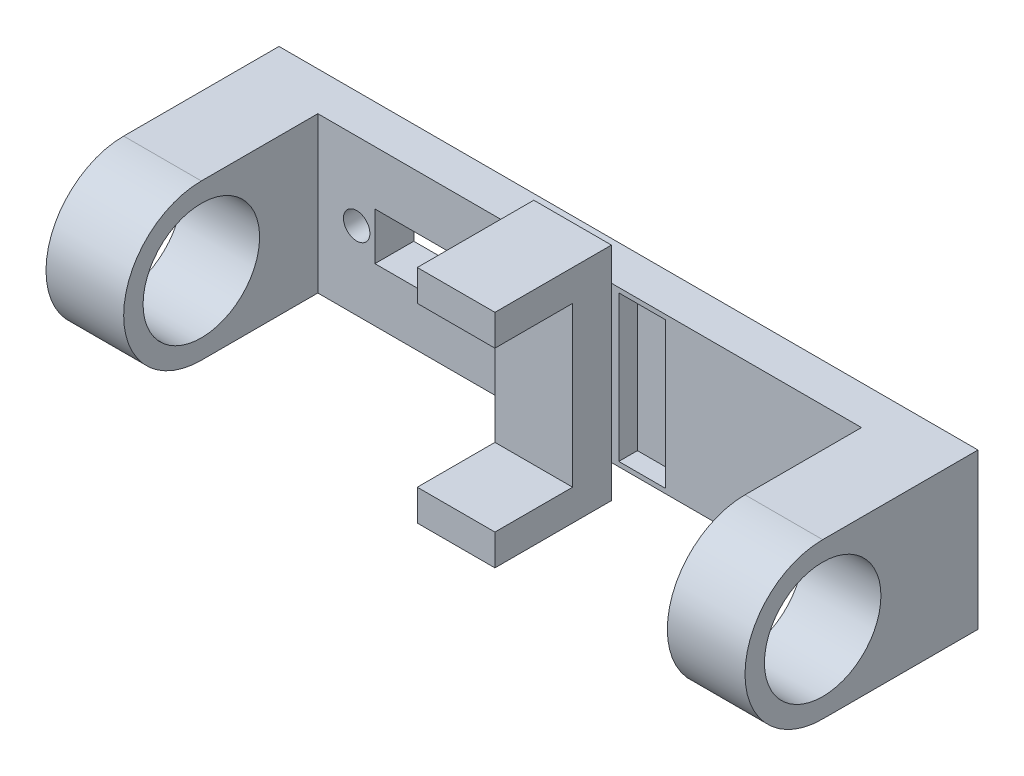
SolidWorks part; units mm, degrees
ref_plane "Plan de face" through (0, 0, 0) normal (0, 0, 1) x (1, 0, 0)
ref_plane "Plan de dessus" through (0, 0, 0) normal (0, 1, 0) x (1, 0, 0)
ref_plane "Plan de droite" through (0, 0, 0) normal (1, 0, 0) x (0, 0, -1)
sketch "Esquisse1" plane through (0, 0, 0) normal (0, 0, 1) x (1, 0, 0)
  line L1 (0, 0) -> (90, 0)
  line L2 (0, 0) -> (0, 20)
  line L3 (0, 20) -> (90, 20)
  line L4 (90, 0) -> (90, 20)
  dimension "D1" = 90
  dimension "D2" = 20
extrude "Boss.-Extru.1" add sketch "Esquisse1" along normal blind 5
sketch "Esquisse2" plane through (0, 0, 5) normal (0, 0, 1) x (1, 0, 0)
  line L0 (90, 20) -> (0, 20) construction
  line L1 (0, 0) -> (10, 0)
  line L2 (0, 0) -> (0, 20)
  line L3 (0, 20) -> (10, 20)
  line L4 (10, 0) -> (10, 20)
  dimension "D1" = 10
extrude "Boss.-Extru.2" add sketch "Esquisse2" along normal blind 30
sketch "Esquisse3" plane through (0, 0, 0) normal (-1, 0, 0) x (0, 0, 1)
  line L0 (0, 20) -> (0, 0) construction
  line L1 (35, 20) -> (0, 20) construction
  line L2 (35, 20) -> (35, 0) construction
  line L3 (35, 0) -> (0, 0) construction
  line L4 (35, 20) -> (20, 20)
  line L5 (35, 20) -> (35, 0)
  line L6 (35, 0) -> (20, 0)
  circle A0 centre (20, 10) radius 7.5
  arc A1 (20, 0) -> (20, 20) centre (20, 10) ccw
  dimension "D2" = 15
  dimension "D4" = 20
  dimension "D1" = 20
  dimension "D3" = 10
extrude "Enlèv. mat.-Extru.1" cut sketch "Esquisse3" against normal up to surface (10 mm away) up to face at (10, 10, 20)
ref_plane "Plan1" through (45, 0, 0) normal (1, 0, 0) x (0, 0, -1)
mirror "Symétrie1" about plane through (45, 0, 0) normal (1, 0, 0) of "Enlèv. mat.-Extru.1", "Boss.-Extru.2"
sketch "Esquisse5" plane through (0, 0, 5) normal (0, 0, 1) x (1, 0, 0)
  line L0 (80, 20) -> (10, 20) construction
  line L1 (48.75, 19.4) -> (54.75, 19.4)
  line L2 (48.75, 19.4) -> (48.75, 0.6)
  line L3 (48.75, 0.6) -> (54.75, 0.6)
  line L4 (54.75, 19.4) -> (54.75, 0.6)
  line L10 (45, -11) -> (45, 11) construction
  point P7 (51.75, 19.4)
  point P9 (53.3, 0.7904)
  dimension "D1" = 18.8
  dimension "D2" = 6
  dimension "D3" = 0.6
  dimension "D4" = 6.75
extrude "Enlèv. mat.-Extru.2" cut sketch "Esquisse5" against normal offset from surface (2.4 mm away) 2.6 up to face at (45, 10, 0)
sketch "Esquisse6" plane through (0, 0, 5) normal (0, 0, 1) x (1, 0, 0)
  line L0 (80, 20) -> (10, 20) construction
  line L1 (10, 0) -> (10, 20) construction
  line L2 (80, 20) -> (80, 0) construction
  circle A0 centre (25, 10) radius 1.5 construction
  circle A1 centre (68, 10) radius 1.5
  dimension "D1" = 3
  dimension "D4" = 3
  dimension "D2" = 10
  dimension "D3" = 15
  dimension "D5" = 10
  dimension "D6" = 12
extrude "Enlèv. mat.-Extru.3" [suppressed] cut sketch "Esquisse6" against normal up to surface (5 mm away)
sketch "Esquisse10" plane through (0, 0, 5) normal (0, 0, 1) x (1, 0, 0)
  line L0 (48.75, 19.4) -> (48.75, 0.6) construction
  line L1 (17.35, 13.05) -> (32.35, 13.05)
  line L2 (17.35, 13.05) -> (17.35, 6.95)
  line L3 (17.35, 6.95) -> (32.35, 6.95)
  line L4 (32.35, 13.05) -> (32.35, 6.95)
  line L5 (80, 20) -> (10, 20) construction
  point P6 (32.35, 10)
  dimension "D1" = 16.4
  dimension "D2" = 15
  dimension "D3" = 6.1
  dimension "D4" = 10
extrude "Enlèv. mat.-Extru.4" cut sketch "Esquisse10" against normal up to surface (5 mm away) up to face at (45, 10, 0)
sketch "Esquisse11" plane through (0, 0, 5) normal (0, 0, 1) x (1, 0, 0)
  line L0 (0, 10) -> (91.8744, 10) construction
  line L2 (45, -11) -> (45, 11) construction
  line L4 (0, 20) -> (0, 0)
  line L5 (90, 20) -> (0, 20)
  line L6 (90, 0) -> (90, 20)
  line L7 (0, 0) -> (90, 0)
  line L8 (0, 20) -> (0, 0) construction
  line L9 (90, 20) -> (0, 20) construction
  line L10 (90, 0) -> (90, 20) construction
  line L11 (0, 0) -> (90, 0) construction
  circle A0 centre (15, 10) radius 1
  circle A1 centre (75, 10) radius 1
  dimension "D2" = 2
  dimension "D3" = 2
  dimension "D4" = 30
  dimension "D5" = 30
  dimension "D1" = 0
extrude "Enlèv. mat.-Extru.5" cut sketch "Esquisse11" against normal blind 10
hole_wizard "Dégagement M31" positions "Esquisse12" profile "Esquisse13" hole size "M3" standard "ISO" end condition through all
sketch "Esquisse12" plane through (0, 0, 5) normal (0, 0, 1) x (1, 0, 0)
  point P0 (15, 10)
  point P3 (75, 10)
sketch "Esquisse13" plane through (15, 10, 5) normal (1, 0, 0) x (0, -1, 0)
  line L0 (0, 0) -> (0, 5)
  line L1 (0, 5) -> (1.7, 5)
  line L2 (1.7, 5) -> (1.7, 0)
  line L5 (1.7, 0) -> (0, 0)
  line L11 (0, -6.35) -> (0, 107.95) construction
  dimension "Diamètre du perçage jusqu'au prochain" = 3.4
  dimension "Profondeur du perçage jusqu'au prochain" = 5
sketch "Esquisse14" plane through (0, 0, 5) normal (0, 0, 1) x (1, 0, 0)
  line L0 (10, 0) -> (80, 0) construction
  line L1 (37.8031, 24.2512) -> (47.8031, 24.2512)
  line L2 (37.8031, 24.2512) -> (37.8031, -4.2488)
  line L3 (37.8031, -4.2488) -> (47.8031, -4.2488)
  line L4 (47.8031, 24.2512) -> (47.8031, -4.2488)
  line L6 (45, -11) -> (45, 11) construction
  point P4 (37.8031, 10.0012)
  point P7 (42.8031, 24.2512)
  dimension "D1" = 28.5
  dimension "D2" = 10.0012
  dimension "D3" = 10
  dimension "D4" = 2.1969
extrude "Boss.-Extru.3" add sketch "Esquisse14" along normal blind 5
sketch "Esquisse16" plane through (0, 0, 10) normal (0, 0, 1) x (1, 0, 0)
  line L0 (47.8031, 0) -> (47.8031, 20) construction
  line L1 (37.8031, 24.2512) -> (47.8031, 24.2512)
  line L2 (37.8031, 24.2512) -> (37.8031, 20.2512)
  line L3 (37.8031, 20.2512) -> (47.8031, 20.2512)
  line L4 (47.8031, 24.2512) -> (47.8031, 20.2512)
  line L6 (37.8031, -4.2488) -> (47.8031, -4.2488)
  line L7 (37.8031, -4.2488) -> (37.8031, -0.2488)
  line L8 (37.8031, -0.2488) -> (47.8031, -0.2488)
  line L9 (47.8031, -4.2488) -> (47.8031, -0.2488)
  dimension "D1" = 4
  dimension "D2" = 4
extrude "Boss.-Extru.4" add sketch "Esquisse16" along normal blind 10
equation "\"D3@Esquisse5\"=(20-\"D1@Esquisse5\")/2"
